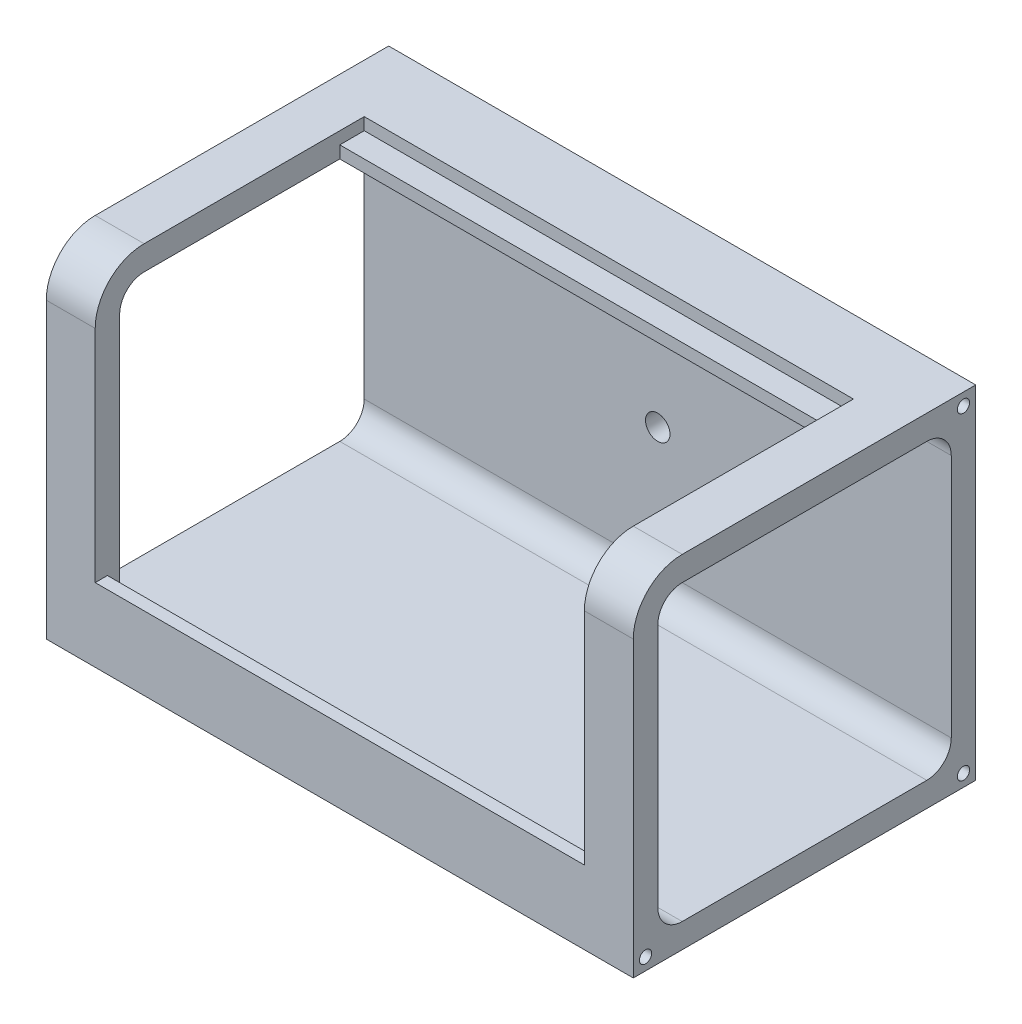
SolidWorks part; units mm, degrees
ref_plane "前视基准面" through (0, 0, 0) normal (0, 0, 1) x (1, 0, 0)
ref_plane "上视基准面" through (0, 0, 0) normal (0, 1, 0) x (1, 0, 0)
ref_plane "右视基准面" through (0, 0, 0) normal (1, 0, 0) x (0, 0, -1)
other "Configuration Table"
sketch "草图1" plane through (0, 0, 0) normal (1, 0, 0) x (0, 0, -1)
  line L7 (10, 0) -> (110, 0)
  line L8 (0, 10) -> (0, 110)
  line L9 (10, 120) -> (110, 120)
  line L10 (120, 10) -> (120, 110)
  line L11 (10, 130) -> (130, 130)
  line L12 (-10, 110) -> (-10, -10)
  line L13 (-10, -10) -> (130, -10)
  line L14 (130, 130) -> (130, -10)
  arc A0 (10, 0) -> (0, 10) centre (10, 10) cw
  arc A1 (110, 0) -> (120, 10) centre (110, 10) ccw
  arc A2 (110, 120) -> (120, 110) centre (110, 110) cw
  arc A3 (0, 110) -> (10, 120) centre (10, 110) cw
  arc A4 (-10, 110) -> (10, 130) centre (10, 110) cw
  point P10 (0, 0)
  point P11 (0, 0)
  point P14 (0, 0)
  point P17 (120, 0)
  point P20 (120, 120)
  dimension "D7" = 10
  dimension "D8" = 20
  dimension "D1" = 120
  dimension "D2" = 120
  dimension "D3" = 140
  dimension "D4" = 140
  dimension "D5" = 10
  dimension "D6" = 10
extrude "凸台-拉伸1" add sketch "草图1" along normal blind 20
sketch "草图2" plane through (20, 0, 0) normal (1, 0, 0) x (0, 0, -1)
  line L0 (130, 130) -> (10, 130) construction
  line L1 (130, -10) -> (130, 130) construction
  line L2 (-10, -10) -> (130, -10) construction
  line L3 (-10, 110) -> (-10, -10) construction
  line L21 (120, 10) -> (120, 110) construction
  line L22 (10, 0) -> (110, 0) construction
  line L30 (110, 120) -> (10, 120) construction
  line L31 (130, 130) -> (100, 130)
  line L33 (130, -10) -> (130, 130)
  line L34 (-10, -10) -> (130, -10)
  line L35 (-10, 10) -> (-10, -10)
  line L36 (120, 10) -> (120, 110)
  line L37 (10, 0) -> (110, 0)
  line L39 (110, 120) -> (107.4215, 120)
  line L40 (100, 130) -> (100, 125)
  line L42 (107.4215, 120) -> (90, 120)
  line L43 (90, 120) -> (90, 125)
  line L44 (90, 125) -> (100, 125)
  line L45 (-5, 10) -> (0, 10)
  line L46 (-10, 10) -> (-10, 20)
  line L47 (-10, 20) -> (-5, 20)
  line L48 (-5, 20) -> (-5, 10)
  arc A5 (120, 110) -> (110, 120) centre (110, 110) ccw construction
  arc A6 (110, 0) -> (120, 10) centre (110, 10) ccw construction
  arc A7 (0, 10) -> (10, 0) centre (10, 10) ccw construction
  arc A17 (120, 110) -> (110, 120) centre (110, 110) ccw
  arc A18 (110, 0) -> (120, 10) centre (110, 10) ccw
  arc A19 (0, 10) -> (10, 0) centre (10, 10) ccw
  dimension "D4" = 10
  dimension "D5" = 10
  dimension "D1" = 30
  dimension "D2" = 5
  dimension "D3" = 5
extrude "凸台-拉伸2" add sketch "草图2" along normal blind 200
sketch "草图3" plane through (220, 0, 0) normal (1, 0, 0) x (0, 0, -1)
  line L4 (130, 130) -> (10, 130)
  line L5 (130, -10) -> (130, 130)
  line L6 (-10, -10) -> (130, -10)
  line L7 (-10, 110) -> (-10, -10)
  line L8 (130, 130) -> (10, 130)
  line L9 (130, -10) -> (130, 130)
  line L10 (-10, -10) -> (130, -10)
  line L11 (-10, 110) -> (-10, -10)
  line L12 (0, 110) -> (0, 10)
  line L13 (10, 0) -> (110, 0)
  line L14 (120, 10) -> (120, 110)
  line L15 (110, 120) -> (10, 120)
  line L16 (0, 110) -> (0, 10)
  line L17 (10, 0) -> (110, 0)
  line L18 (120, 10) -> (120, 110)
  line L19 (110, 120) -> (10, 120)
  arc A1 (10, 130) -> (-10, 110) centre (10, 110) ccw
  arc A2 (10, 130) -> (-10, 110) centre (10, 110) ccw
  arc A6 (0, 10) -> (10, 0) centre (10, 10) ccw
  arc A7 (110, 0) -> (120, 10) centre (110, 10) ccw
  arc A8 (120, 110) -> (110, 120) centre (110, 110) ccw
  arc A9 (10, 120) -> (0, 110) centre (10, 110) ccw
  arc A10 (0, 10) -> (10, 0) centre (10, 10) ccw
  arc A11 (110, 0) -> (120, 10) centre (110, 10) ccw
  arc A12 (120, 110) -> (110, 120) centre (110, 110) ccw
  arc A13 (10, 120) -> (0, 110) centre (10, 110) ccw
  dimension "D1" = 0
  dimension "D2" = 0
extrude "凸台-拉伸3" add sketch "草图3" along normal blind 20
sketch "草图5" plane through (240, 0, 0) normal (1, 0, 0) x (0, 0, -1)
  line L0 (-10, 110) -> (-10, -10) construction
  line L1 (-10, -10) -> (130, -10) construction
  line L2 (130, -10) -> (130, 130) construction
  line L3 (130, 130) -> (10, 130) construction
  circle A0 centre (-5, -5) radius 2.5
  circle A1 centre (125, -5) radius 2.5
  circle A2 centre (125, 125) radius 2.5
  dimension "D3" = 5
  dimension "D4" = 5
  dimension "D5" = 5
  dimension "D1" = 5
  dimension "D2" = 5
  dimension "D6" = 5
  dimension "D7" = 5
  dimension "D8" = 5
  dimension "D9" = 5
extrude "切除-拉伸1" cut sketch "草图5" against normal blind 10
sketch "草图6" plane through (0, 0, 0) normal (-1, 0, 0) x (0, 0, 1)
  circle A1 centre (-125, 125) radius 2.5
  circle A2 centre (-125, 125) radius 2.5
  circle A3 centre (-125, -5) radius 2.5
  circle A4 centre (-125, -5) radius 2.5
  circle A5 centre (5, -5) radius 2.5
  circle A6 centre (5, -5) radius 2.5
  dimension "D1" = 0
  dimension "D2" = 0
  dimension "D3" = 0
extrude "切除-拉伸2" cut sketch "草图6" against normal blind 10
sketch "草图7" plane through (0, 0, -120) normal (0, 0, 1) x (1, 0, 0)
  line L0 (0, 110) -> (0, -10) construction
  line L1 (240, -10) -> (0, -10) construction
  circle A0 centre (120, 60) radius 5
  dimension "D3" = 10
  dimension "D1" = 120
  dimension "D2" = 70
extrude "切除-拉伸3" cut sketch "草图7" against normal up to next
